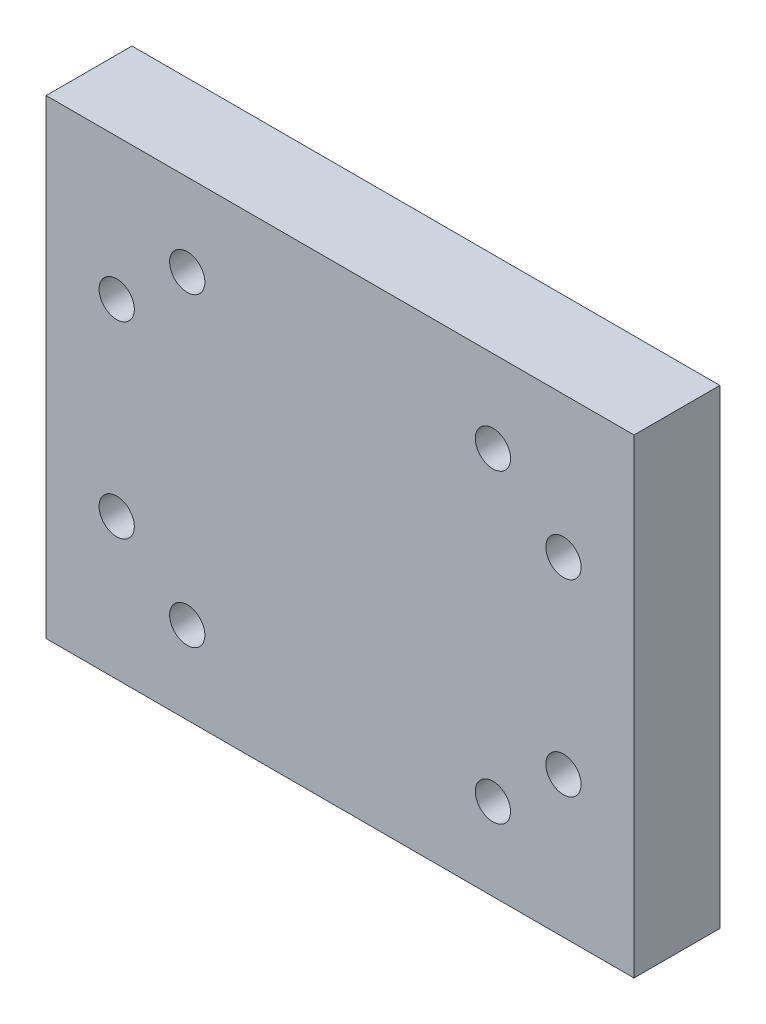
SolidWorks part; units mm, degrees
ref_plane "Front Plane" through (0, 0, 0) normal (0, 0, 1) x (1, 0, 0)
ref_plane "Top Plane" through (0, 0, 0) normal (0, 1, 0) x (1, 0, 0)
ref_plane "Right Plane" through (0, 0, 0) normal (1, 0, 0) x (0, 0, -1)
sketch "Sketch1" plane through (0, 0, 0) normal (0, 0, 1) x (1, 0, 0)
  line L0 (0, 20) -> (0, 0) construction
  line L1 (25, -20) -> (-25, -20)
  line L2 (25, -20) -> (25, 20)
  line L3 (25, 20) -> (-25, 20)
  line L4 (-25, -20) -> (-25, 20)
  line L5 (25, -20) -> (-25, 20) construction
  line L6 (25, 20) -> (-25, -20) construction
  line L7 (0, 0) -> (25, 0) construction
  circle A0 centre (-13, 13) radius 1.5
  circle A1 centre (13, 13) radius 1.5
  circle A2 centre (13, -13) radius 1.5
  circle A3 centre (-13, -13) radius 1.5
  point P0 (0, 0)
  dimension "D3" = 26
  dimension "D4" = 3
  dimension "D5" = 26
  dimension "D1" = 50
  dimension "D2" = 40
extrude "Boss-Extrude1" add sketch "Sketch1" along normal blind 7.3
sketch "Sketch2" plane through (0, 0, 7.3) normal (0, 0, 1) x (1, 0, 0)
  line L0 (0, 20) -> (0, 0) construction
  line L1 (25, 20) -> (-25, 20) construction
  line L2 (0, 0) -> (25, 0) construction
  line L3 (25, -20) -> (25, 20) construction
  circle A0 centre (-19, 8) radius 1.5
  circle A1 centre (19, 8) radius 1.5
  circle A2 centre (19, -8) radius 1.5
  circle A3 centre (-19, -8) radius 1.5
  dimension "D3" = 3
  dimension "D1" = 38
  dimension "D2" = 16
extrude "Cut-Extrude1" cut sketch "Sketch2" against normal through all both and the other way through all
